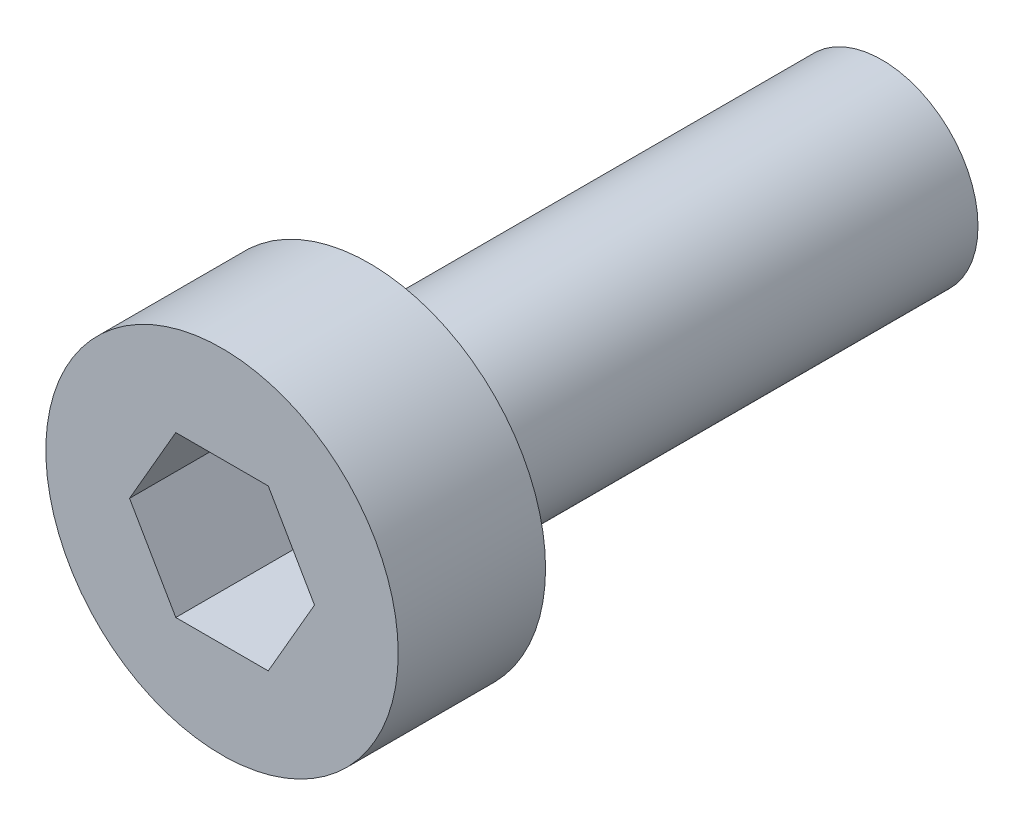
SolidWorks part; units mm, degrees
ref_plane "Plan de face" through (0, 0, 0) normal (0, 0, 1) x (1, 0, 0)
ref_plane "Plan de dessus" through (0, 0, 0) normal (0, 1, 0) x (1, 0, 0)
ref_plane "Plan de droite" through (0, 0, 0) normal (1, 0, 0) x (0, 0, -1)
sketch "Esquisse1" plane through (0, 0, 0) normal (0, 0, 1) x (1, 0, 0)
  circle A0 centre (0, 0) radius 1.5
  dimension "D1" = 3
extrude "Boss.-Extru.1" add sketch "Esquisse1" along normal blind 8
sketch "Esquisse2" plane through (0, 0, 8) normal (0, 0, 1) x (1, 0, 0)
  circle A0 centre (0, 0) radius 2.75
  dimension "D1" = 5.5
extrude "Boss.-Extru.2" add sketch "Esquisse2" along normal blind 2.3
sketch "Esquisse3" plane through (0, 0, 10.3) normal (0, 0, 1) x (1, 0, 0)
  line L1 (1.4434, 0) -> (0.7217, 1.25)
  line L2 (0.7217, 1.25) -> (-0.7217, 1.25)
  line L3 (-0.7217, 1.25) -> (-1.4434, 0)
  line L4 (-1.4434, 0) -> (-0.7217, -1.25)
  line L5 (-0.7217, -1.25) -> (0.7217, -1.25)
  line L6 (0.7217, -1.25) -> (1.4434, 0)
  circle A0 centre (0, 0) radius 1.25 construction
  dimension "D1" = 2.5
extrude "Enlèv. mat.-Extru.1" cut sketch "Esquisse3" against normal blind 2
